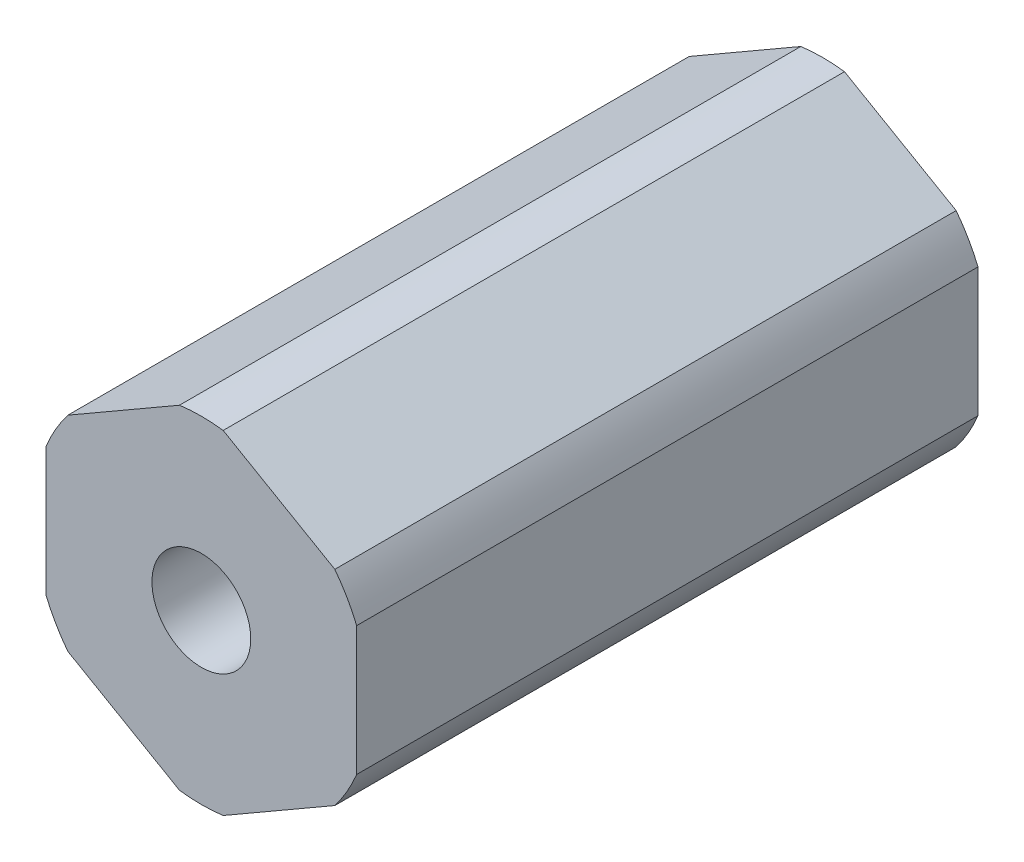
SolidWorks part; units mm, degrees
material "7075-T6 (SN)"
ref_plane "Front Plane" through (0, 0, 0) normal (0, 0, 1) x (1, 0, 0)
ref_plane "Top Plane" through (0, 0, 0) normal (0, 1, 0) x (1, 0, 0)
ref_plane "Right Plane" through (0, 0, 0) normal (1, 0, 0) x (0, 0, -1)
sketch "Sketch1" plane through (0, 0, 0) normal (0, 0, 1) x (1, 0, 0)
  line L1 (0, 7.3323) -> (-6.35, 3.6662)
  line L2 (-6.35, 3.6662) -> (-6.35, -3.6662)
  line L3 (-6.35, -3.6662) -> (0, -7.3323)
  line L4 (0, -7.3323) -> (6.35, -3.6662)
  line L5 (6.35, -3.6662) -> (6.35, 3.6662)
  line L6 (6.35, 3.6662) -> (0, 7.3323)
  circle A0 centre (0, 0) radius 6.35 construction
  circle A1 centre (0, 0) radius 6.875
  circle A2 centre (0, 0) radius 2.0193
  dimension "D1" = 12.7
  dimension "D2" = 4.0386
  dimension "D3" = 13.75
extrude "Boss-Extrude1" add sketch "Sketch1" along normal blind 25.4 contours L5 A1 L6 L1 L2 L3 L4 A2
hole_wizard "#10-32 Tapped Hole1" positions "3DSketch2" profile "Sketch3" tap size "#10-32" standard "ANSI Inch"
sketch3d "3DSketch2"
  circle A0 centre (0, 0, 0) radius 2.0193 construction
  circle A1 centre (0, 0, 25.4) radius 2.0193 construction
  point P0 (0, 0, 25.4)
  point P2 (0, 0, 0)
  point P7 (0, 0, 2.0193)
  point P10 (0, 0, 27.4193)
sketch "Sketch3" plane through (0, 0, 25.4) normal (1, 0, 0) x (0, -1, 0)
  line L0 (0, 0) -> (0, 13.2428)
  line L1 (0, 13.2428) -> (2.0193, 12.0294)
  line L2 (2.0193, 12.0294) -> (2.0193, 0)
  line L5 (2.0193, 0) -> (0, 0)
  line L10 (0, 13.2428) -> (-2.0193, 12.0294) construction
  line L11 (0, -6.35) -> (0, 107.95) construction
  dimension "Tap Drill Dia." = 4.0386
  dimension "Tap Drill Depth" = 12.0294
  dimension "Drill Angle" = 118
cosmetic thread "Hole Thread1" parameters "D1"=9.652, "D2"=4.826
cosmetic thread "Hole Thread2" parameters "D1"=9.652, "D2"=4.826
equation "\"D3@Sketch1\"=13.75mm"
